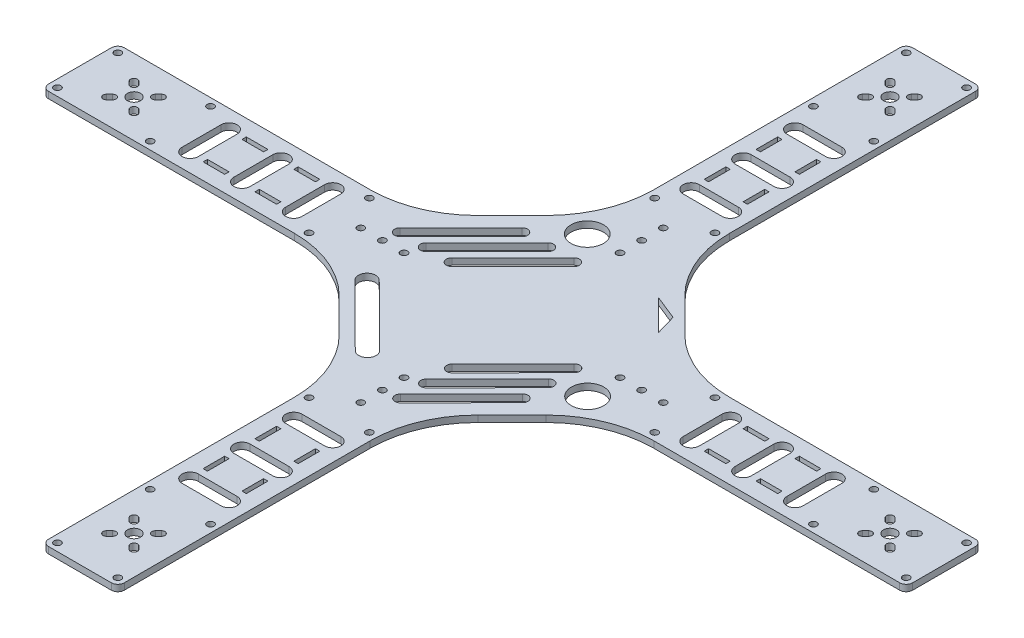
SolidWorks part; units mm, degrees
ref_plane "前视基准面" through (0, 0, 0) normal (0, 0, 1) x (1, 0, 0)
ref_plane "上视基准面" through (0, 0, 0) normal (0, 1, 0) x (1, 0, 0)
ref_plane "右视基准面" through (0, 0, 0) normal (1, 0, 0) x (0, 0, -1)
other "Configuration Table"
sketch "基本底盘" plane through (0, 0, 0) normal (0, 1, 0) x (1, 0, 0)
  line L0 (0, 0) -> (0, -350) construction
  line L1 (4.9497, -4.9497) -> (6.364, -6.364) construction
  line L4 (6.0811, -3.8184) -> (7.4953, -5.2326)
  line L5 (3.8184, -6.0811) -> (5.2326, -7.4953)
  line L6 (-17.5, 25) -> (17.5, 25)
  line L9 (-4.9497, -4.9497) -> (-6.364, -6.364) construction
  line L10 (-3.8184, -6.0811) -> (-5.2326, -7.4953)
  line L11 (-6.0811, -3.8184) -> (-7.4953, -5.2326)
  line L12 (-17.5, 25) -> (-17.5, -25)
  line L15 (-4.9497, 4.9497) -> (-6.364, 6.364) construction
  line L16 (-6.0811, 3.8184) -> (-7.4953, 5.2326)
  line L17 (-3.8184, 6.0811) -> (-5.2326, 7.4953)
  line L18 (17.5, 25) -> (17.5, -25)
  line L21 (4.9497, 4.9497) -> (6.364, 6.364) construction
  line L22 (3.8184, 6.0811) -> (5.2326, 7.4953)
  line L23 (6.0811, 3.8184) -> (7.4953, 5.2326)
  line L24 (0, -25) -> (0, -35)
  line L25 (-9, -35) -> (9, -35) construction
  line L26 (-9, -59) -> (9, -59) construction
  line L27 (-17.5, -25) -> (17.5, -25) construction
  line L28 (-17.5, 25) -> (17.5, -25) construction
  line L29 (17.5, 25) -> (-17.5, -25) construction
  line L30 (-17.5, 25) -> (-13.9645, 21.4645)
  line L31 (-17.5, 0) -> (17.5, 0) construction
  line L32 (-80, -175) -> (80, -175)
  line L33 (0, -95) -> (0, -255)
  line L34 (-32.1447, -127.1447) -> (-47.8553, -142.8553)
  line L35 (32.1447, -222.8553) -> (47.8553, -207.1447)
  line L36 (47.8553, -142.8553) -> (32.1447, -127.1447)
  line L37 (-47.8553, -207.1447) -> (-32.1447, -222.8553)
  line L38 (-13.9645, -21.4645) -> (-13.9645, -95) construction
  line L39 (-17.5, -25) -> (-17.5, -91.7893)
  line L40 (17.5, -25) -> (17.5, -91.7893)
  line L41 (0, -95) -> (0, -105)
  line L42 (-9, -31.25) -> (9, -31.25)
  line L43 (-9, -38.75) -> (9, -38.75)
  line L44 (-9, -55.25) -> (9, -55.25)
  line L45 (-9, -62.75) -> (9, -62.75)
  line L46 (-9, -83) -> (9, -83) construction
  line L47 (-9, -79.25) -> (9, -79.25)
  line L48 (-9, -86.75) -> (9, -86.75)
  line L49 (9, -38.75) -> (9, -55.25)
  line L50 (8, -42) -> (10, -42)
  line L51 (8, -42) -> (8, -52)
  line L52 (10, -42) -> (10, -52)
  line L53 (8, -52) -> (10, -52)
  line L54 (8, -42) -> (10, -52) construction
  line L55 (10, -42) -> (8, -52) construction
  line L56 (8, -66) -> (10, -76) construction
  line L57 (10, -66) -> (8, -76) construction
  line L58 (8, -66) -> (10, -66)
  line L59 (8, -66) -> (8, -76)
  line L60 (8, -76) -> (10, -76)
  line L61 (10, -66) -> (10, -76)
  line L62 (-8, -66) -> (-8, -76)
  line L63 (-8, -76) -> (-10, -76)
  line L64 (-10, -66) -> (-10, -76)
  line L65 (-8, -66) -> (-10, -66)
  line L66 (-8, -52) -> (-10, -52)
  line L67 (-8, -42) -> (-8, -52)
  line L68 (-8, -42) -> (-10, -42)
  line L69 (-10, -42) -> (-10, -52)
  line L70 (200, -157.5) -> (200, -192.5)
  line L71 (200, -157.5) -> (150, -157.5)
  line L72 (200, -192.5) -> (150, -192.5)
  line L73 (150, -175) -> (140, -175)
  line L74 (200, -157.5) -> (196.4645, -161.0355)
  line L75 (136.25, -184) -> (119.75, -184)
  line L76 (133, -183) -> (133, -185)
  line L77 (133, -183) -> (123, -183)
  line L78 (133, -185) -> (123, -185)
  line L79 (123, -183) -> (123, -185)
  line L80 (109, -183) -> (109, -185)
  line L81 (109, -183) -> (99, -183)
  line L82 (99, -183) -> (99, -185)
  line L83 (109, -185) -> (99, -185)
  line L84 (109, -167) -> (99, -167)
  line L85 (99, -167) -> (99, -165)
  line L86 (109, -165) -> (99, -165)
  line L87 (109, -167) -> (109, -165)
  line L88 (123, -167) -> (123, -165)
  line L89 (133, -167) -> (123, -167)
  line L90 (133, -167) -> (133, -165)
  line L91 (133, -165) -> (123, -165)
  line L92 (150, -157.5) -> (150, -192.5) construction
  line L93 (200, -157.5) -> (150, -192.5) construction
  line L94 (200, -192.5) -> (150, -157.5) construction
  line L95 (175, -157.5) -> (175, -192.5) construction
  line L96 (153.5355, -161.0355) -> (80, -161.0355) construction
  line L97 (133, -183) -> (123, -185) construction
  line L98 (133, -185) -> (123, -183) construction
  line L99 (109, -183) -> (99, -185) construction
  line L100 (109, -185) -> (99, -183) construction
  line L101 (150, -157.5) -> (83.2107, -157.5)
  line L102 (150, -192.5) -> (83.2107, -192.5)
  line L103 (170.0503, -179.9497) -> (168.636, -181.364) construction
  line L104 (171.1816, -181.0811) -> (169.7674, -182.4953)
  line L105 (168.9189, -178.8184) -> (167.5047, -180.2326)
  line L106 (170.0503, -170.0503) -> (168.636, -168.636) construction
  line L107 (168.9189, -171.1816) -> (167.5047, -169.7674)
  line L108 (171.1816, -168.9189) -> (169.7674, -167.5047)
  line L109 (179.9497, -170.0503) -> (181.364, -168.636) construction
  line L110 (178.8184, -168.9189) -> (180.2326, -167.5047)
  line L111 (181.0811, -171.1816) -> (182.4953, -169.7674)
  line L112 (179.9497, -179.9497) -> (181.364, -181.364) construction
  line L113 (181.0811, -178.8184) -> (182.4953, -180.2326)
  line L114 (178.8184, -181.0811) -> (180.2326, -182.4953)
  line L115 (140, -166) -> (140, -184) construction
  line L116 (143.75, -166) -> (143.75, -184)
  line L117 (136.25, -166) -> (136.25, -184)
  line L118 (116, -166) -> (116, -184) construction
  line L119 (119.75, -166) -> (119.75, -184)
  line L120 (112.25, -166) -> (112.25, -184)
  line L121 (92, -166) -> (92, -184) construction
  line L122 (95.75, -166) -> (95.75, -184)
  line L123 (88.25, -166) -> (88.25, -184)
  line L124 (17.5, -375) -> (-17.5, -375)
  line L125 (17.5, -375) -> (17.5, -325)
  line L126 (-17.5, -375) -> (-17.5, -325)
  line L127 (0, -325) -> (0, -315)
  line L128 (17.5, -375) -> (13.9645, -371.4645)
  line L129 (-9, -311.25) -> (-9, -294.75)
  line L130 (-8, -308) -> (-10, -308)
  line L131 (-8, -308) -> (-8, -298)
  line L132 (-10, -308) -> (-10, -298)
  line L133 (-8, -298) -> (-10, -298)
  line L134 (-8, -284) -> (-10, -284)
  line L135 (-8, -284) -> (-8, -274)
  line L136 (-8, -274) -> (-10, -274)
  line L137 (-10, -284) -> (-10, -274)
  line L138 (8, -284) -> (8, -274)
  line L139 (8, -274) -> (10, -274)
  line L140 (10, -284) -> (10, -274)
  line L141 (8, -284) -> (10, -284)
  line L142 (8, -298) -> (10, -298)
  line L143 (8, -308) -> (8, -298)
  line L144 (8, -308) -> (10, -308)
  line L145 (10, -308) -> (10, -298)
  line L146 (17.5, -325) -> (-17.5, -325) construction
  line L147 (17.5, -375) -> (-17.5, -325) construction
  line L148 (-17.5, -375) -> (17.5, -325) construction
  line L149 (17.5, -350) -> (-17.5, -350) construction
  line L150 (13.9645, -328.5355) -> (13.9645, -255) construction
  line L151 (-8, -308) -> (-10, -298) construction
  line L152 (-10, -308) -> (-8, -298) construction
  line L153 (-8, -284) -> (-10, -274) construction
  line L154 (-10, -284) -> (-8, -274) construction
  line L155 (17.5, -325) -> (17.5, -258.2107)
  line L156 (-17.5, -325) -> (-17.5, -258.2107)
  line L157 (-4.9497, -345.0503) -> (-6.364, -343.636) construction
  line L158 (-6.0811, -346.1816) -> (-7.4953, -344.7674)
  line L159 (-3.8184, -343.9189) -> (-5.2326, -342.5047)
  line L160 (4.9497, -345.0503) -> (6.364, -343.636) construction
  line L161 (3.8184, -343.9189) -> (5.2326, -342.5047)
  line L162 (6.0811, -346.1816) -> (7.4953, -344.7674)
  line L163 (4.9497, -354.9497) -> (6.364, -356.364) construction
  line L164 (6.0811, -353.8184) -> (7.4953, -355.2326)
  line L165 (3.8184, -356.0811) -> (5.2326, -357.4953)
  line L166 (-4.9497, -354.9497) -> (-6.364, -356.364) construction
  line L167 (-3.8184, -356.0811) -> (-5.2326, -357.4953)
  line L168 (-6.0811, -353.8184) -> (-7.4953, -355.2326)
  line L169 (9, -315) -> (-9, -315) construction
  line L170 (9, -318.75) -> (-9, -318.75)
  line L171 (9, -311.25) -> (-9, -311.25)
  line L172 (9, -291) -> (-9, -291) construction
  line L173 (9, -294.75) -> (-9, -294.75)
  line L174 (9, -287.25) -> (-9, -287.25)
  line L175 (9, -267) -> (-9, -267) construction
  line L176 (9, -270.75) -> (-9, -270.75)
  line L177 (9, -263.25) -> (-9, -263.25)
  line L178 (-200, -192.5) -> (-200, -157.5)
  line L179 (-200, -192.5) -> (-150, -192.5)
  line L180 (-200, -157.5) -> (-150, -157.5)
  line L181 (-150, -175) -> (-140, -175)
  line L182 (-200, -192.5) -> (-196.4645, -188.9645)
  line L183 (-136.25, -166) -> (-119.75, -166)
  line L184 (-133, -167) -> (-133, -165)
  line L185 (-133, -167) -> (-123, -167)
  line L186 (-133, -165) -> (-123, -165)
  line L187 (-123, -167) -> (-123, -165)
  line L188 (-109, -167) -> (-109, -165)
  line L189 (-109, -167) -> (-99, -167)
  line L190 (-99, -167) -> (-99, -165)
  line L191 (-109, -165) -> (-99, -165)
  line L192 (-109, -183) -> (-99, -183)
  line L193 (-99, -183) -> (-99, -185)
  line L194 (-109, -185) -> (-99, -185)
  line L195 (-109, -183) -> (-109, -185)
  line L196 (-123, -183) -> (-123, -185)
  line L197 (-133, -183) -> (-123, -183)
  line L198 (-133, -183) -> (-133, -185)
  line L199 (-133, -185) -> (-123, -185)
  line L200 (-150, -192.5) -> (-150, -157.5) construction
  line L201 (-200, -192.5) -> (-150, -157.5) construction
  line L202 (-200, -157.5) -> (-150, -192.5) construction
  line L203 (-175, -192.5) -> (-175, -157.5) construction
  line L204 (-153.5355, -188.9645) -> (-80, -188.9645) construction
  line L205 (-133, -167) -> (-123, -165) construction
  line L206 (-133, -165) -> (-123, -167) construction
  line L207 (-109, -167) -> (-99, -165) construction
  line L208 (-109, -165) -> (-99, -167) construction
  line L209 (-150, -192.5) -> (-83.2107, -192.5)
  line L210 (-150, -157.5) -> (-83.2107, -157.5)
  line L211 (-170.0503, -170.0503) -> (-168.636, -168.636) construction
  line L212 (-171.1816, -168.9189) -> (-169.7674, -167.5047)
  line L213 (-168.9189, -171.1816) -> (-167.5047, -169.7674)
  line L214 (-170.0503, -179.9497) -> (-168.636, -181.364) construction
  line L215 (-168.9189, -178.8184) -> (-167.5047, -180.2326)
  line L216 (-171.1816, -181.0811) -> (-169.7674, -182.4953)
  line L217 (-179.9497, -179.9497) -> (-181.364, -181.364) construction
  line L218 (-178.8184, -181.0811) -> (-180.2326, -182.4953)
  line L219 (-181.0811, -178.8184) -> (-182.4953, -180.2326)
  line L220 (-179.9497, -170.0503) -> (-181.364, -168.636) construction
  line L221 (-181.0811, -171.1816) -> (-182.4953, -169.7674)
  line L222 (-178.8184, -168.9189) -> (-180.2326, -167.5047)
  line L223 (-140, -184) -> (-140, -166) construction
  line L224 (-143.75, -184) -> (-143.75, -166)
  line L225 (-136.25, -184) -> (-136.25, -166)
  line L226 (-116, -184) -> (-116, -166) construction
  line L227 (-119.75, -184) -> (-119.75, -166)
  line L228 (-112.25, -184) -> (-112.25, -166)
  line L229 (-92, -184) -> (-92, -166) construction
  line L230 (-95.75, -184) -> (-95.75, -166)
  line L231 (-88.25, -184) -> (-88.25, -166)
  line L232 (0, -95) -> (-32.1447, -127.1447)
  line L233 (0, -95) -> (32.1447, -127.1447)
  line L234 (47.8553, -142.8553) -> (80, -175)
  line L235 (47.8553, -207.1447) -> (80, -175)
  line L236 (-80, -175) -> (-47.8553, -207.1447)
  line L237 (-80, -175) -> (-47.8553, -142.8553)
  line L238 (-32.1447, -222.8553) -> (0, -255)
  line L239 (0, -255) -> (32.1447, -222.8553)
  circle A0 centre (0, 0) radius 8 construction
  arc A3 (6.0811, -3.8184) -> (3.8184, -6.0811) centre (4.9497, -4.9497) ccw
  arc A4 (5.2326, -7.4953) -> (7.4953, -5.2326) centre (6.364, -6.364) ccw
  arc A7 (-3.8184, -6.0811) -> (-6.0811, -3.8184) centre (-4.9497, -4.9497) ccw
  arc A8 (-7.4953, -5.2326) -> (-5.2326, -7.4953) centre (-6.364, -6.364) ccw
  arc A11 (-6.0811, 3.8184) -> (-3.8184, 6.0811) centre (-4.9497, 4.9497) ccw
  arc A12 (-5.2326, 7.4953) -> (-7.4953, 5.2326) centre (-6.364, 6.364) ccw
  arc A15 (3.8184, 6.0811) -> (6.0811, 3.8184) centre (4.9497, 4.9497) ccw
  arc A16 (7.4953, 5.2326) -> (5.2326, 7.4953) centre (6.364, 6.364) ccw
  circle A17 centre (0, 0) radius 14 construction
  arc A18 (-9, -31.25) -> (-9, -38.75) centre (-9, -35) ccw
  arc A19 (9, -38.75) -> (9, -31.25) centre (9, -35) ccw
  circle A20 centre (0, 0) radius 3
  circle A21 centre (0, 0) radius 88.9 construction
  circle A22 centre (0, 0) radius 64.77 construction
  circle A23 centre (-13.9645, 21.4645) radius 1.6
  circle A24 centre (13.9645, 21.4645) radius 1.6
  circle A25 centre (13.9645, -21.4645) radius 1.6
  circle A26 centre (-13.9645, -21.4645) radius 1.6
  circle A27 centre (-13.9645, -95) radius 1.6
  circle A28 centre (13.9645, -95) radius 1.6
  circle A29 centre (0, -105) radius 1.6
  arc A30 (-9, -55.25) -> (-9, -62.75) centre (-9, -59) ccw
  arc A31 (9, -62.75) -> (9, -55.25) centre (9, -59) ccw
  arc A32 (-9, -79.25) -> (-9, -86.75) centre (-9, -83) ccw
  arc A33 (9, -86.75) -> (9, -79.25) centre (9, -83) ccw
  circle A34 centre (175, -175) radius 3
  circle A35 centre (196.4645, -161.0355) radius 1.6
  circle A36 centre (196.4645, -188.9645) radius 1.6
  circle A37 centre (153.5355, -188.9645) radius 1.6
  circle A38 centre (153.5355, -161.0355) radius 1.6
  circle A39 centre (80, -161.0355) radius 1.6
  circle A40 centre (80, -188.9645) radius 1.6
  circle A41 centre (175, -175) radius 8 construction
  circle A42 centre (175, -175) radius 14 construction
  circle A43 centre (175, -175) radius 88.9 construction
  circle A44 centre (175, -175) radius 64.77 construction
  circle A45 centre (70, -175) radius 1.6
  arc A46 (171.1816, -181.0811) -> (168.9189, -178.8184) centre (170.0503, -179.9497) ccw
  arc A47 (167.5047, -180.2326) -> (169.7674, -182.4953) centre (168.636, -181.364) ccw
  arc A48 (168.9189, -171.1816) -> (171.1816, -168.9189) centre (170.0503, -170.0503) ccw
  arc A49 (169.7674, -167.5047) -> (167.5047, -169.7674) centre (168.636, -168.636) ccw
  arc A50 (178.8184, -168.9189) -> (181.0811, -171.1816) centre (179.9497, -170.0503) ccw
  arc A51 (182.4953, -169.7674) -> (180.2326, -167.5047) centre (181.364, -168.636) ccw
  arc A52 (181.0811, -178.8184) -> (178.8184, -181.0811) centre (179.9497, -179.9497) ccw
  arc A53 (180.2326, -182.4953) -> (182.4953, -180.2326) centre (181.364, -181.364) ccw
  arc A54 (143.75, -166) -> (136.25, -166) centre (140, -166) ccw
  arc A55 (136.25, -184) -> (143.75, -184) centre (140, -184) ccw
  arc A56 (119.75, -166) -> (112.25, -166) centre (116, -166) ccw
  arc A57 (112.25, -184) -> (119.75, -184) centre (116, -184) ccw
  arc A58 (95.75, -166) -> (88.25, -166) centre (92, -166) ccw
  arc A59 (88.25, -184) -> (95.75, -184) centre (92, -184) ccw
  circle A60 centre (0, -350) radius 3
  circle A61 centre (13.9645, -371.4645) radius 1.6
  circle A62 centre (-13.9645, -371.4645) radius 1.6
  circle A63 centre (-13.9645, -328.5355) radius 1.6
  circle A64 centre (13.9645, -328.5355) radius 1.6
  circle A65 centre (13.9645, -255) radius 1.6
  circle A66 centre (-13.9645, -255) radius 1.6
  circle A67 centre (0, -350) radius 8 construction
  circle A68 centre (0, -350) radius 14 construction
  circle A69 centre (0, -350) radius 88.9 construction
  circle A70 centre (0, -350) radius 64.77 construction
  circle A71 centre (0, -245) radius 1.6
  arc A72 (-6.0811, -346.1816) -> (-3.8184, -343.9189) centre (-4.9497, -345.0503) ccw
  arc A73 (-5.2326, -342.5047) -> (-7.4953, -344.7674) centre (-6.364, -343.636) ccw
  arc A74 (3.8184, -343.9189) -> (6.0811, -346.1816) centre (4.9497, -345.0503) ccw
  arc A75 (7.4953, -344.7674) -> (5.2326, -342.5047) centre (6.364, -343.636) ccw
  arc A76 (6.0811, -353.8184) -> (3.8184, -356.0811) centre (4.9497, -354.9497) ccw
  arc A77 (5.2326, -357.4953) -> (7.4953, -355.2326) centre (6.364, -356.364) ccw
  arc A78 (-3.8184, -356.0811) -> (-6.0811, -353.8184) centre (-4.9497, -354.9497) ccw
  arc A79 (-7.4953, -355.2326) -> (-5.2326, -357.4953) centre (-6.364, -356.364) ccw
  arc A80 (9, -318.75) -> (9, -311.25) centre (9, -315) ccw
  arc A81 (-9, -311.25) -> (-9, -318.75) centre (-9, -315) ccw
  arc A82 (9, -294.75) -> (9, -287.25) centre (9, -291) ccw
  arc A83 (-9, -287.25) -> (-9, -294.75) centre (-9, -291) ccw
  arc A84 (9, -270.75) -> (9, -263.25) centre (9, -267) ccw
  arc A85 (-9, -263.25) -> (-9, -270.75) centre (-9, -267) ccw
  circle A86 centre (-175, -175) radius 3
  circle A87 centre (-196.4645, -188.9645) radius 1.6
  circle A88 centre (-196.4645, -161.0355) radius 1.6
  circle A89 centre (-153.5355, -161.0355) radius 1.6
  circle A90 centre (-153.5355, -188.9645) radius 1.6
  circle A91 centre (-80, -188.9645) radius 1.6
  circle A92 centre (-80, -161.0355) radius 1.6
  circle A93 centre (-175, -175) radius 8 construction
  circle A94 centre (-175, -175) radius 14 construction
  circle A95 centre (-175, -175) radius 88.9 construction
  circle A96 centre (-175, -175) radius 64.77 construction
  circle A97 centre (-70, -175) radius 1.6
  arc A98 (-171.1816, -168.9189) -> (-168.9189, -171.1816) centre (-170.0503, -170.0503) ccw
  arc A99 (-167.5047, -169.7674) -> (-169.7674, -167.5047) centre (-168.636, -168.636) ccw
  arc A100 (-168.9189, -178.8184) -> (-171.1816, -181.0811) centre (-170.0503, -179.9497) ccw
  arc A101 (-169.7674, -182.4953) -> (-167.5047, -180.2326) centre (-168.636, -181.364) ccw
  arc A102 (-178.8184, -181.0811) -> (-181.0811, -178.8184) centre (-179.9497, -179.9497) ccw
  arc A103 (-182.4953, -180.2326) -> (-180.2326, -182.4953) centre (-181.364, -181.364) ccw
  arc A104 (-181.0811, -171.1816) -> (-178.8184, -168.9189) centre (-179.9497, -170.0503) ccw
  arc A105 (-180.2326, -167.5047) -> (-182.4953, -169.7674) centre (-181.364, -168.636) ccw
  arc A106 (-143.75, -184) -> (-136.25, -184) centre (-140, -184) ccw
  arc A107 (-136.25, -166) -> (-143.75, -166) centre (-140, -166) ccw
  arc A108 (-119.75, -184) -> (-112.25, -184) centre (-116, -184) ccw
  arc A109 (-112.25, -166) -> (-119.75, -166) centre (-116, -166) ccw
  arc A110 (-95.75, -184) -> (-88.25, -184) centre (-92, -184) ccw
  arc A111 (-88.25, -166) -> (-95.75, -166) centre (-92, -166) ccw
  arc A112 (17.5, -258.2107) -> (32.1447, -222.8553) centre (67.5, -258.2107) cw
  arc A113 (-17.5, -258.2107) -> (-32.1447, -222.8553) centre (-67.5, -258.2107) ccw
  arc A114 (47.8553, -142.8553) -> (83.2107, -157.5) centre (83.2107, -107.5) ccw
  arc A115 (83.2107, -192.5) -> (47.8553, -207.1447) centre (83.2107, -242.5) ccw
  arc A116 (-47.8553, -207.1447) -> (-83.2107, -192.5) centre (-83.2107, -242.5) ccw
  arc A117 (-47.8553, -142.8553) -> (-83.2107, -157.5) centre (-83.2107, -107.5) cw
  arc A118 (32.1447, -127.1447) -> (17.5, -91.7893) centre (67.5, -91.7893) cw
  arc A119 (-32.1447, -127.1447) -> (-17.5, -91.7893) centre (-67.5, -91.7893) ccw
  point P14 (5.6569, -5.6569)
  point P28 (-5.6569, -5.6569)
  point P34 (0, 0)
  point P42 (-5.6569, 5.6569)
  point P48 (0, -175)
  point P53 (0, -175)
  point P56 (5.6569, 5.6569)
  point P61 (0, 0)
  point P63 (0, 8)
  point P73 (0, -35)
  point P80 (0, -59)
  point P87 (0, -83)
  point P93 (9, -47)
  point P95 (9, -71)
  point P125 (169.3431, -180.6569)
  point P139 (169.3431, -169.3431)
  point P145 (175, -175)
  point P152 (180.6569, -169.3431)
  point P161 (180.6569, -180.6569)
  point P166 (175, -175)
  point P177 (140, -175)
  point P184 (116, -175)
  point P191 (92, -175)
  point P197 (128, -184)
  point P199 (104, -184)
  point P226 (-5.6569, -344.3431)
  point P240 (5.6569, -344.3431)
  point P246 (0, -350)
  point P253 (5.6569, -355.6569)
  point P262 (-5.6569, -355.6569)
  point P267 (0, -350)
  point P278 (0, -315)
  point P285 (0, -291)
  point P292 (0, -267)
  point P298 (-9, -303)
  point P300 (-9, -279)
  point P327 (-169.3431, -169.3431)
  point P341 (-169.3431, -180.6569)
  point P347 (-175, -175)
  point P354 (-180.6569, -180.6569)
  point P363 (-180.6569, -169.3431)
  point P368 (-175, -175)
  point P379 (-140, -175)
  point P386 (-116, -175)
  point P393 (-92, -175)
  point P399 (-128, -166)
  point P401 (-104, -166)
  point P416 (0, -175)
  dimension "D1" = 16
  dimension "D3" = 28
  dimension "D2" = 6
  dimension "D4" = 350
  dimension "D5" = 129.54
  dimension "D9" = 3.2
  dimension "D11" = 3.2
  dimension "D12" = 10
  dimension "D13" = 3.2
  dimension "D14" = 10
  dimension "D15" = 3
  dimension "D20" = 50
  dimension "D6" = 35
  dimension "D7" = 50
  dimension "D8" = 5
  dimension "D10" = 2
  dimension "D16" = 2
  dimension "D17" = 10
  dimension "D18" = 2
  dimension "D19" = 4
extrude "凸台-拉伸1" add sketch "基本底盘" along normal blind 3
fillet "圆角3" radius 3 8 edges at (200, 1.5, 157.5) (200, 1.5, 192.5) (17.5, 1.5, 375) (-17.5, 1.5, 375) (-200, 1.5, 192.5) (-200, 1.5, 157.5) (-17.5, 1.5, -25) (17.5, 1.5, -25)
sketch "草图1" plane through (0, 3, 0) normal (0, 1, 0) x (1, 0, 0)
  line L0 (-33.4628, -208.5466) -> (33.4628, -141.4534) construction
  line L1 (50, -175) -> (50, -190) construction
  line L2 (-51.2007, -190.6995) -> (16.1183, -123.3805) construction
  line L3 (-51.2007, -190.6995) -> (-15.8454, -226.0549) construction
  line L4 (16.1183, -123.3805) -> (51.4736, -158.7359) construction
  line L5 (-15.8454, -226.0549) -> (51.4736, -158.7359) construction
  line L6 (26.7033, -133.9655) -> (40.8887, -148.1509)
  line L7 (40.8887, -148.1509) -> (38.1115, -138.5443)
  line L8 (38.1115, -138.5443) -> (26.7033, -133.9655)
  line L9 (-47.6177, -194.501) -> (-19.308, -222.5923) construction
  line L10 (-17.5412, -157.04) -> (-21.0767, -153.5045)
  line L11 (-44.8002, -191.6616) -> (-16.4905, -219.7529)
  line L12 (-50.4351, -197.3404) -> (-22.1254, -225.4316)
  line L13 (-35.2189, -167.6466) -> (-6.9346, -139.3624) construction
  line L14 (-47.2189, -167.6466) -> (-18.9346, -139.3624) construction
  line L15 (-36.9866, -165.8789) -> (-8.7024, -137.5946)
  line L16 (-33.4511, -169.4144) -> (-5.1668, -141.1301)
  line L17 (-48.9866, -165.8789) -> (-20.7024, -137.5946)
  line L18 (-45.4511, -169.4144) -> (-17.1668, -141.1301)
  line L19 (-59.2189, -167.6466) -> (-30.9346, -139.3624) construction
  line L20 (-60.9866, -165.8789) -> (-32.7024, -137.5946)
  line L21 (-57.4511, -169.4144) -> (-29.1668, -141.1301)
  line L22 (7.4414, -210.2004) -> (35.6549, -181.8454) construction
  line L23 (9.2136, -211.9637) -> (37.4271, -183.6088)
  line L24 (5.6693, -208.437) -> (33.8827, -180.0821)
  line L25 (7.5015, -234.2003) -> (35.7149, -205.8454) construction
  line L26 (9.2737, -235.9636) -> (37.4871, -207.6087)
  line L27 (5.7293, -232.437) -> (33.9427, -204.082)
  line L28 (7.4715, -222.2003) -> (35.6849, -193.8454) construction
  line L29 (9.2436, -223.9637) -> (37.4571, -195.6087)
  line L30 (5.6993, -220.437) -> (33.9127, -192.0821)
  line L31 (0, -105) -> (0, -115)
  line L32 (0, -95) -> (0, -255) construction
  arc A0 (-44.8002, -191.6616) -> (-50.4351, -197.3404) centre (-47.6177, -194.501) ccw
  arc A1 (-22.1254, -225.4316) -> (-16.4905, -219.7529) centre (-19.308, -222.5923) ccw
  arc A2 (-36.9866, -165.8789) -> (-33.4511, -169.4144) centre (-35.2189, -167.6466) ccw
  arc A3 (-5.1668, -141.1301) -> (-8.7024, -137.5946) centre (-6.9346, -139.3624) ccw
  arc A4 (-48.9866, -165.8789) -> (-45.4511, -169.4144) centre (-47.2189, -167.6466) ccw
  arc A5 (-17.1668, -141.1301) -> (-20.7024, -137.5946) centre (-18.9346, -139.3624) ccw
  arc A6 (-60.9866, -165.8789) -> (-57.4511, -169.4144) centre (-59.2189, -167.6466) ccw
  arc A7 (-29.1668, -141.1301) -> (-32.7024, -137.5946) centre (-30.9346, -139.3624) ccw
  arc A8 (9.2136, -211.9637) -> (5.6693, -208.437) centre (7.4414, -210.2004) cw
  arc A9 (33.8827, -180.0821) -> (37.4271, -183.6088) centre (35.6549, -181.8454) cw
  arc A10 (9.2737, -235.9636) -> (5.7293, -232.437) centre (7.5015, -234.2003) cw
  arc A11 (33.9427, -204.082) -> (37.4871, -207.6087) centre (35.7149, -205.8454) cw
  arc A12 (9.2436, -223.9637) -> (5.6993, -220.437) centre (7.4715, -222.2003) cw
  arc A13 (33.9127, -192.0821) -> (37.4571, -195.6087) centre (35.6849, -193.8454) cw
  circle A14 centre (0, -115) radius 1.6
  circle A15 centre (0, -125) radius 1.6
  circle A16 centre (60, -175) radius 1.6
  circle A17 centre (50, -175) radius 1.6
  circle A18 centre (0, -235) radius 1.6
  circle A19 centre (0, -225) radius 1.6
  circle A20 centre (-60, -175) radius 1.6
  circle A21 centre (-50, -175) radius 1.6
  circle A23 centre (50, -190) radius 7.5
  circle A24 centre (-15.125, -125.0377) radius 7.5
  point P4 (0, -175)
  point P5 (0, -175)
  point P9 (33.796, -141.0582)
  point P18 (-33.4628, -208.5466)
  point P27 (-21.0767, -153.5045)
  point P34 (-33.0767, -153.5045)
  point P41 (-45.0767, -153.5045)
  point P46 (21.5482, -196.0229)
  point P53 (21.6082, -220.0228)
  point P60 (21.5782, -208.0229)
  point P87 (0, -175)
  dimension "D4" = 5
  dimension "D7" = 3.2
  dimension "D10" = 15
  dimension "D11" = 15
  dimension "D1" = 50
  dimension "D2" = 10
  dimension "D3" = 10
  dimension "D5" = 3
  dimension "D6" = 10
  dimension "D8" = 2
  dimension "D9" = 4
extrude "切除-拉伸1" cut sketch "草图1" against normal blind 10
